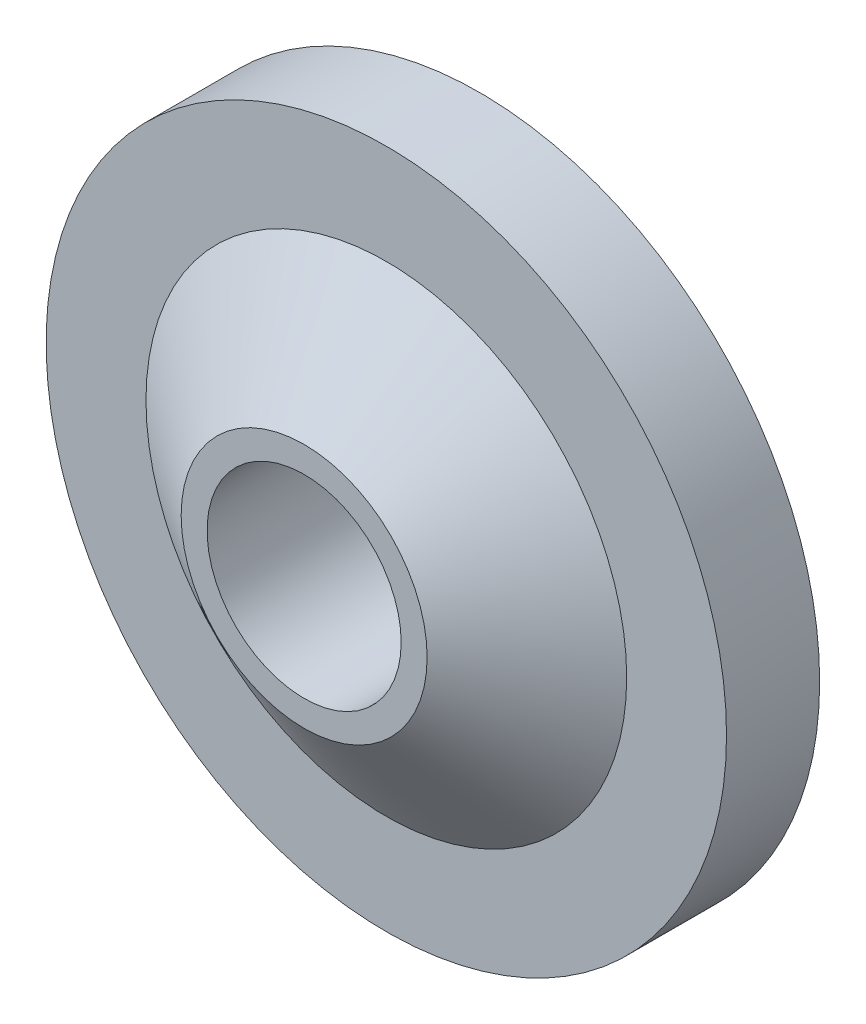
SolidWorks part; units mm, degrees
material "Rubber"
ref_plane "Front Plane" through (0, 0, 0) normal (0, 0, 1) x (1, 0, 0)
ref_plane "Top Plane" through (0, 0, 0) normal (0, 1, 0) x (1, 0, 0)
ref_plane "Right Plane" through (0, 0, 0) normal (1, 0, 0) x (0, 0, -1)
sketch "Sketch1" plane through (0, 0, 0) normal (0, 0, 1) x (1, 0, 0)
  circle A0 centre (0, 0) radius 62.09
extrude "Boss-Extrude1" add sketch "Sketch1" along normal blind 17 and the other way blind 10 draft 70
sketch "Sketch2" plane through (0, 0, 17) normal (0, 0, 1) x (1, 0, 0)
  circle A0 centre (0, 0) radius 43.87
extrude "Boss-Extrude2" add sketch "Sketch2" along normal blind 15 draft 55
sketch "Sketch3" plane through (0, 0, 32) normal (0, 0, 1) x (1, 0, 0)
  circle A0 centre (0, 0) radius 17.71
extrude "Cut-Extrude1" cut sketch "Sketch3" against normal through all
